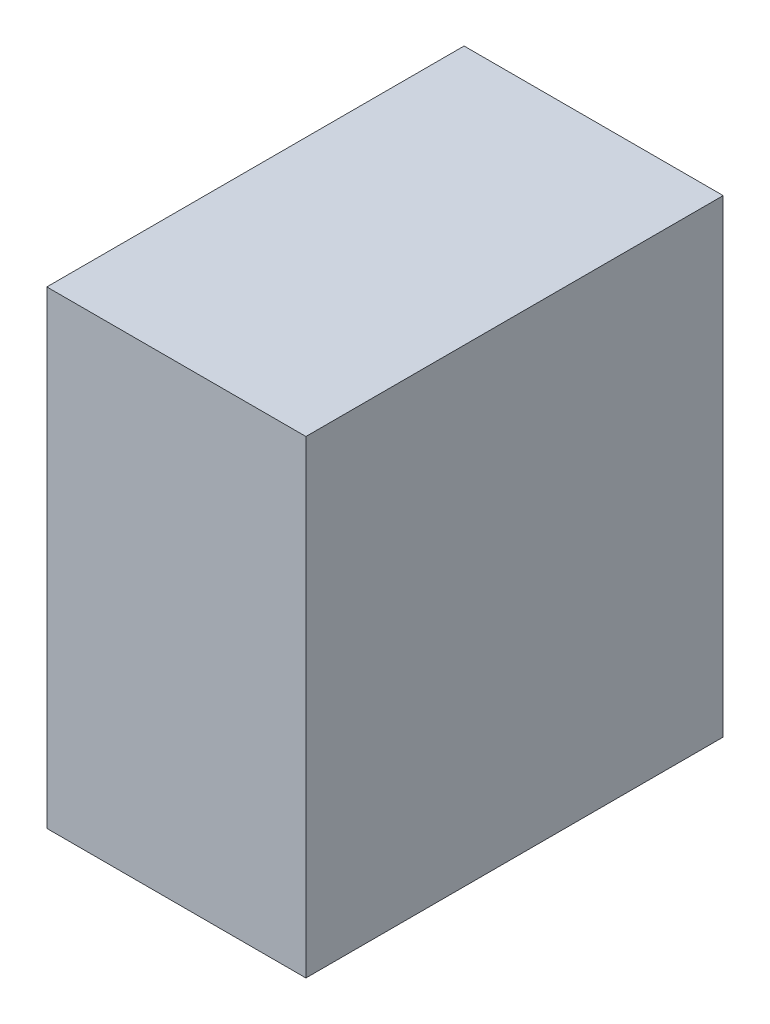
SolidWorks part; units mm, degrees
ref_plane "Front Plane" through (0, 0, 0) normal (1, 0, 0) x (0, 1, 0)
ref_plane "Top Plane" through (0, 0, 0) normal (0, 0, 1) x (0, 1, 0)
ref_plane "Right Plane" through (0, 0, 0) normal (0, 1, 0) x (-1, 0, 0)
sketch "Sketch1" plane through (0, 0, 0) normal (1, 0, 0) x (0, 1, 0)
  line L1 (0, 0) -> (153, 0)
  line L2 (0, 0) -> (0, 134.8)
  line L3 (0, 134.8) -> (153, 134.8)
  line L4 (153, 0) -> (153, 134.8)
  dimension "D1" = 153
  dimension "D2" = 134.8
extrude "Boss-Extrude1" add sketch "Sketch1" along normal blind 85.2
shell "Shell1" thickness 1.5
sketch "Sketch2" plane through (0, 0, 0) normal (0, -1, 0) x (1, 0, 0)
  line L1 (0, 134.8) -> (85.2, 134.8)
  line L2 (0, 134.8) -> (0, 0)
  line L3 (0, 0) -> (85.2, 0)
  line L4 (85.2, 134.8) -> (85.2, 0)
extrude "Cut-Extrude1" cut sketch "Sketch2" against normal blind 1.5
sketch "Sketch3" plane through (0, 0, 0) normal (-1, 0, 0) x (0, -1, 0)
  line L1 (-153, 134.8) -> (-1.5, 134.8)
  line L2 (-153, 134.8) -> (-153, 0)
  line L3 (-153, 0) -> (-1.5, 0)
  line L4 (-1.5, 134.8) -> (-1.5, 0)
extrude "Cut-Extrude2" cut sketch "Sketch3" against normal blind 1.5
